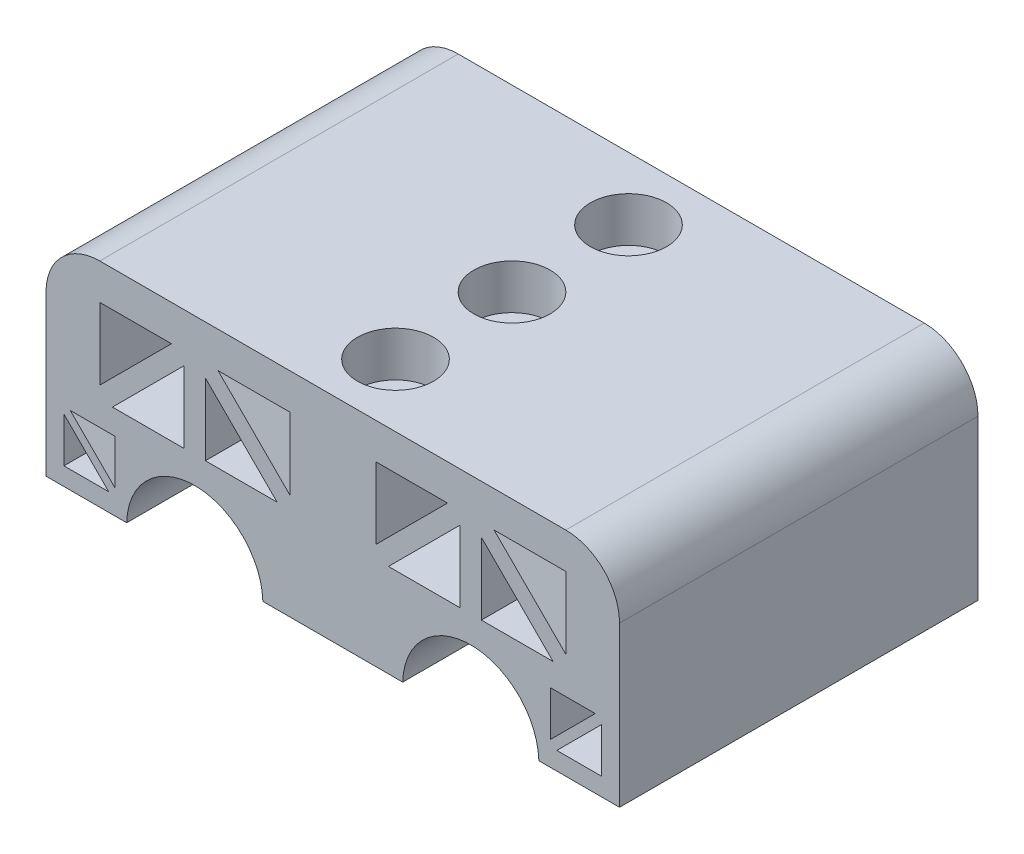
SolidWorks part; units mm, degrees
material "PLA"
ref_plane "Front Plane" through (0, 0, 0) normal (0, 0, 1) x (1, 0, 0)
ref_plane "Top Plane" through (0, 0, 0) normal (0, 1, 0) x (1, 0, 0)
ref_plane "Right Plane" through (0, 0, 0) normal (1, 0, 0) x (0, 0, -1)
sketch "Sketch1" plane through (0, 0, 0) normal (0, 0, 1) x (1, 0, 0)
  line L0 (40.64, -977.14) -> (40.64, 49022.86) construction
  line L1 (0, 0) -> (81.28, 0)
  line L2 (0, 0) -> (0, 30.48)
  line L3 (0, 30.48) -> (81.28, 30.48)
  line L4 (81.28, 0) -> (81.28, 30.48)
  circle A0 centre (21.082, 0) radius 9.652
  circle A2 centre (60.198, 0) radius 9.652
  point P14 (40.64, 30.48)
  dimension "D3" = 19.304
  dimension "D1" = 81.28
  dimension "D2" = 30.48
  dimension "D4" = 19.558
extrude "Boss-Extrude1" add sketch "Sketch1" along normal blind 50.8 contours L1 L0 L3 L2 A0 | L0 L1 A2 L4 L3
sketch "Sketch2" plane through (0, 0, 0) normal (0, -1, 0) x (-1, 0, 0)
  line L1 (0, -50.8) -> (-81.28, -50.8)
  line L2 (0, -50.8) -> (0, 0)
  line L3 (0, 0) -> (-81.28, 0)
  line L4 (-81.28, -50.8) -> (-81.28, 0)
extrude "Cut-Extrude1" cut sketch "Sketch2" against normal blind 0.254
sketch "Sketch3" plane through (0, 30.48, 0) normal (0, 1, 0) x (1, 0, 0)
  line L0 (40.64, -1000) -> (40.64, 49000) construction
  line L1 (0, 0) -> (81.28, 0) construction
  line L2 (0, -25.4) -> (81.28, -25.4) construction
  line L3 (0, -50.8) -> (0, 0) construction
  line L4 (81.28, -50.8) -> (81.28, 0) construction
  circle A0 centre (40.64, -8.89) radius 5.3975
  circle A1 centre (40.64, -41.91) radius 5.3975
  circle A2 centre (40.64, -25.4) radius 5.3975
  point P7 (40.64, 0)
  dimension "D1" = 10.795
  dimension "D2" = 8.89
extrude "Cut-Extrude2" cut sketch "Sketch3" against normal blind 6.35
sketch "Sketch4" plane through (0, 24.13, 0) normal (0, 1, 0) x (1, 0, 0)
  circle A0 centre (40.64, -8.89) radius 3.302
  circle A1 centre (40.64, -41.91) radius 3.302
  circle A2 centre (40.64, -25.4) radius 3.302
  dimension "D1" = 6.604
extrude "Cut-Extrude3" cut sketch "Sketch4" against normal through all and the other way through all
sketch "Sketch5" plane through (0, 0, 50.8) normal (0, 0, 1) x (1, 0, 0)
  line L0 (7.62, 15.24) -> (7.62, 25.4)
  line L1 (7.62, 25.4) -> (17.78, 25.4)
  line L2 (17.78, 25.4) -> (7.62, 15.24)
  line L3 (0, 0.254) -> (0, 30.48) construction
  line L4 (0, 30.48) -> (81.28, 30.48) construction
  line L5 (13.5045, 19.3284) -> (35368.8436, 35374.6675) construction
  line L6 (19.5761, 13.4439) -> (19.5761, 23.6039)
  line L7 (9.4161, 13.4439) -> (19.5761, 13.4439)
  line L8 (19.5761, 23.6039) -> (9.4161, 13.4439)
  line L9 (21.082, -990.348) -> (21.082, 49009.652) construction
  line L10 (22.5879, 23.6039) -> (32.7479, 13.4439)
  line L11 (32.7479, 13.4439) -> (22.5879, 13.4439)
  line L12 (22.5879, 13.4439) -> (22.5879, 23.6039)
  line L13 (24.384, 25.4) -> (34.544, 15.24)
  line L14 (34.544, 25.4) -> (24.384, 25.4)
  line L15 (34.544, 15.24) -> (34.544, 25.4)
  line L16 (40.64, -999.746) -> (40.64, 49000.254) construction
  line L17 (50.5493, 0.254) -> (30.7307, 0.254) construction
  line L18 (46.736, 15.24) -> (46.736, 25.4)
  line L19 (46.736, 25.4) -> (56.896, 25.4)
  line L20 (56.896, 25.4) -> (46.736, 15.24)
  line L21 (58.6921, 13.4439) -> (58.6921, 23.6039)
  line L22 (48.5321, 13.4439) -> (58.6921, 13.4439)
  line L23 (58.6921, 23.6039) -> (48.5321, 13.4439)
  line L24 (61.7039, 23.6039) -> (71.8639, 13.4439)
  line L25 (71.8639, 13.4439) -> (61.7039, 13.4439)
  line L26 (61.7039, 13.4439) -> (61.7039, 23.6039)
  line L27 (63.5, 25.4) -> (73.66, 15.24)
  line L28 (73.66, 25.4) -> (63.5, 25.4)
  line L29 (73.66, 15.24) -> (73.66, 25.4)
  line L33 (5.7167, -999.746) -> (5.7167, 49000.254) construction
  line L34 (11.4333, 0.254) -> (0, 0.254) construction
  line L35 (2.5417, 2.794) -> (8.8917, 2.794)
  line L36 (2.5417, 2.794) -> (2.5417, 9.144)
  line L37 (2.5417, 9.144) -> (8.8917, 2.794)
  line L38 (6.1657, 6.418) -> (8.6249, 3.9587) construction
  line L39 (3.4397, 10.042) -> (9.7897, 3.692)
  line L40 (9.7897, 10.042) -> (9.7897, 3.692)
  line L41 (9.7897, 10.042) -> (3.4397, 10.042)
  line L42 (71.4903, 10.042) -> (77.8403, 10.042)
  line L43 (71.4903, 10.042) -> (71.4903, 3.692)
  line L44 (77.8403, 10.042) -> (71.4903, 3.692)
  line L45 (78.7383, 9.144) -> (72.3883, 2.794)
  line L46 (78.7383, 2.794) -> (78.7383, 9.144)
  line L47 (78.7383, 2.794) -> (72.3883, 2.794)
  arc A0 (30.7307, 0.254) -> (11.4333, 0.254) centre (21.082, 0) ccw construction
  point P18 (21.082, 9.652)
  point P29 (40.64, 0.254)
  point P46 (5.7167, 2.794)
  point P49 (5.7167, 0.254)
  point P61 (75.5633, 2.794)
  dimension "D1" = 10.16
  dimension "D2" = 10.16
  dimension "D3" = 7.62
  dimension "D4" = 5.08
  dimension "D5" = 1.27
  dimension "D6" = 6.35
  dimension "D7" = 6.35
  dimension "D8" = 2.54
  dimension "D9" = 0.635
extrude "Cut-Extrude4" cut sketch "Sketch5" against normal through all
fillet "Fillet1" radius 7.62 2 edges at (81.28, 30.48, 25.4) (0, 30.48, 25.4)
